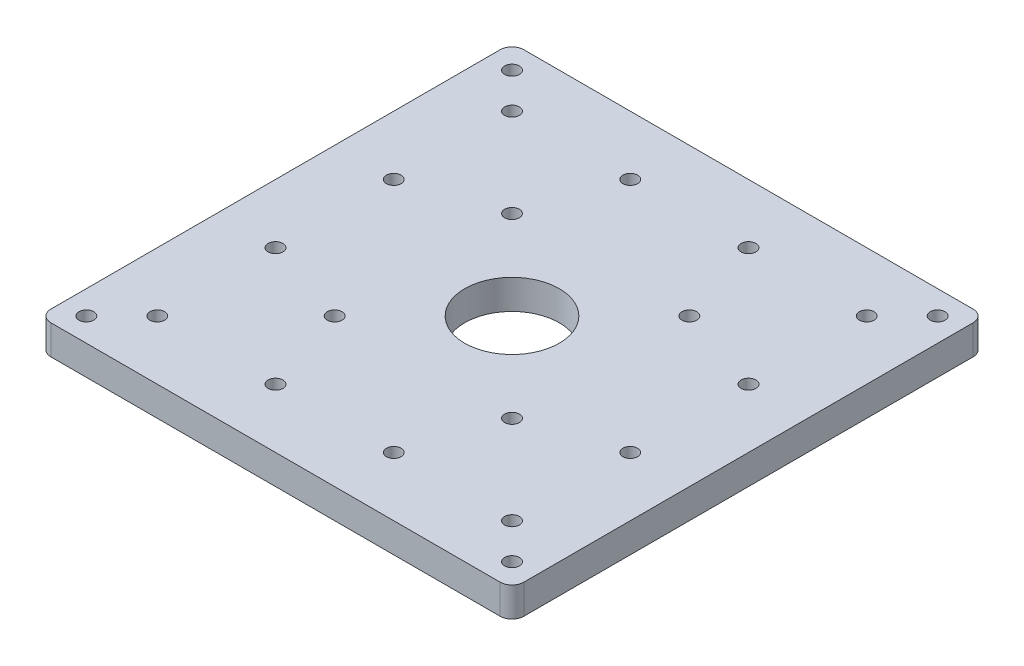
SolidWorks part; units mm, degrees
material "ABS"
ref_plane "Plan de face" through (0, 0, 0) normal (0, 0, 1) x (1, 0, 0)
ref_plane "Plan de dessus" through (0, 0, 0) normal (0, 1, 0) x (1, 0, 0)
ref_plane "Plan de droite" through (0, 0, 0) normal (1, 0, 0) x (0, 0, -1)
sketch "Esquisse1" plane through (0, 0, 0) normal (0, 1, 0) x (1, 0, 0)
  line L0 (0, 0) -> (0, 40) construction
  line L1 (-40, 40) -> (40, 40)
  line L2 (-40, 40) -> (-40, -40)
  line L3 (-40, -40) -> (40, -40)
  line L4 (40, 40) -> (40, -40)
  line L5 (0, 0) -> (40, 0) construction
  circle A0 centre (-15, 15) radius 1.25
  circle A1 centre (15, 15) radius 1.25
  circle A2 centre (-15, -15) radius 1.25
  circle A3 centre (15, -15) radius 1.25
  circle A4 centre (-36, 36) radius 1.25
  circle A5 centre (36, 36) radius 1.25
  circle A6 centre (36, -36) radius 1.25
  circle A7 centre (-36, -36) radius 1.25
  circle A8 centre (0, 0) radius 8
  dimension "D4" = 2.5
  dimension "D7" = 16
  dimension "D1" = 80
  dimension "D2" = 15
  dimension "D3" = 15
  dimension "D5" = 4
  dimension "D6" = 4
extrude "Extrusion1" add sketch "Esquisse1" along normal blind 5
sketch "Esquisse2" plane through (0, 5, 0) normal (0, 1, 0) x (1, 0, 0)
  circle A0 centre (-30, 30) radius 1.25
  dimension "D1" = 2.5
  dimension "D2" = 30
  dimension "D3" = 30
extrude "Enlèv. mat.-Extru.1" cut sketch "Esquisse2" against normal through all
pattern_linear "Répétition linéaire1" count 4 spacing 20 along (0, 0, 1) count 4 spacing 20 along (1, 0, 0) skipping (1, 1), (1, 2), (2, 1), (2, 2) of "Enlèv. mat.-Extru.1"
fillet "Congé1" radius 2 4 edges at (-40, 2.5, -40) (40, 2.5, -40) (40, 2.5, 40) (-40, 2.5, 40)
